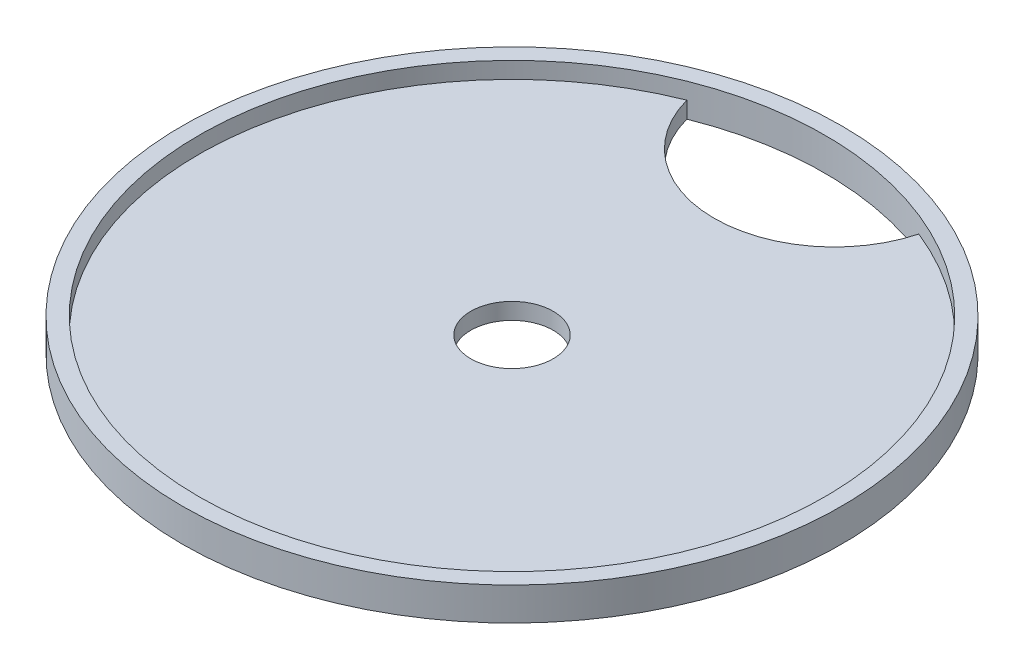
SolidWorks part; units mm, degrees
ref_plane "Front Plane" through (0, 0, 0) normal (0, 0, 1) x (1, 0, 0)
ref_plane "Top Plane" through (0, 0, 0) normal (0, 1, 0) x (1, 0, 0)
ref_plane "Right Plane" through (0, 0, 0) normal (1, 0, 0) x (0, 0, -1)
sketch "Sketch1" plane through (0, 0, 0) normal (0, 1, 0) x (1, 0, 0)
  circle A0 centre (0, 0) radius 40
extrude "Boss-Extrude1" add sketch "Sketch1" along normal blind 40 contours A0
sketch "Sketch2" plane through (0, 40, 0) normal (0, 1, 0) x (1, 0, 0)
  circle A0 centre (0, 0) radius 38
extrude "Cut-Extrude1" cut sketch "Sketch2" against normal blind 38
sketch "Sketch3" plane through (0, 2, 0) normal (0, 1, 0) x (1, 0, 0)
  arc A0 (-14.0761, 35.2968) -> (14.0761, 35.2968) centre (0, 39.1212) ccw
  circle A1 centre (0, 0) radius 38 construction
  circle A2 centre (0, 0) radius 38 construction
  arc A3 (-14.0761, 35.2968) -> (14.0761, 35.2968) centre (0, 0) cw
extrude "Cut-Extrude2" cut sketch "Sketch3" against normal blind 38
sketch "Sketch4" plane through (0, 2, 0) normal (0, 1, 0) x (1, 0, 0)
  circle A0 centre (0, 0) radius 5
extrude "Cut-Extrude3" cut sketch "Sketch4" against normal blind 38
sketch "Sketch6" plane through (0, 0, 0) normal (0, -1, 0) x (1, 0, 0)
  circle A1 centre (-20, 0) radius 2
  circle A2 centre (20, 0) radius 2
  point P11 (20, 2.4497)
extrude "Boss-Extrude2" add sketch "Sketch6" along normal blind 2
sketch "Sketch8" plane through (0, 40, 0) normal (0, 1, 0) x (1, 0, 0)
  circle A0 centre (0, 0) radius 43.4969
extrude "Cut-Extrude4" cut sketch "Sketch8" against normal blind 36
